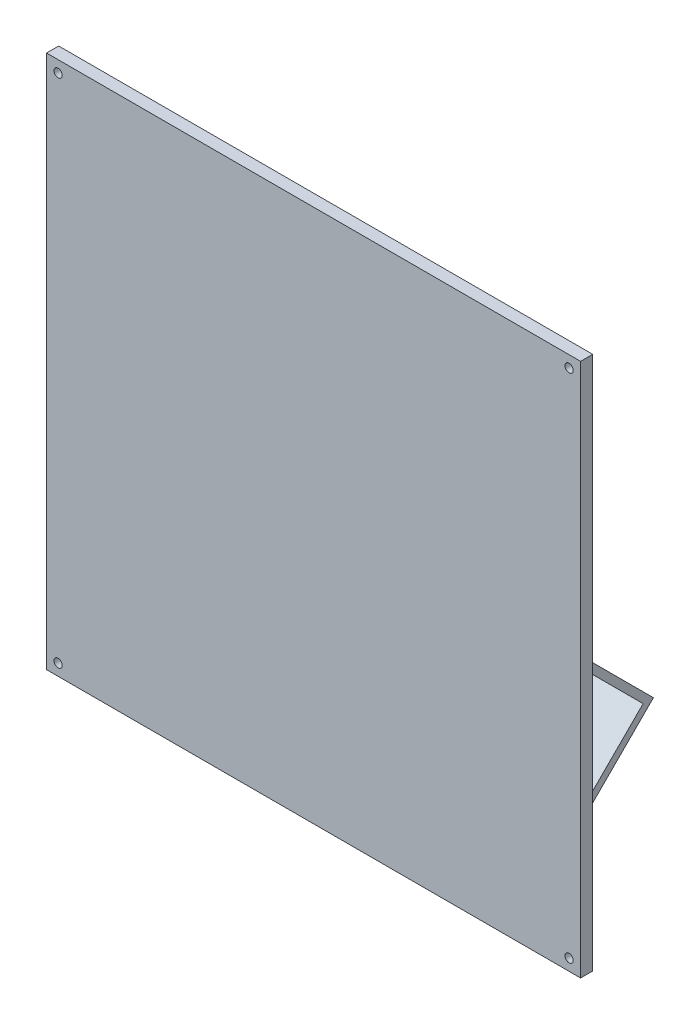
SolidWorks part; units mm, degrees
ref_plane "Přední rovina" through (0, 0, 0) normal (0, 0, 1) x (1, 0, 0)
ref_plane "Horní rovina" through (0, 0, 0) normal (0, 1, 0) x (1, 0, 0)
ref_plane "Pravá rovina" through (0, 0, 0) normal (1, 0, 0) x (0, 0, -1)
sketch "Skica1" plane through (0, 0, 0) normal (0, 0, 1) x (1, 0, 0)
  line L1 (-110, -110) -> (110, -110)
  line L2 (-110, -110) -> (-110, 110)
  line L3 (-110, 110) -> (110, 110)
  line L4 (110, -110) -> (110, 110)
  line L5 (-110, -110) -> (110, 110) construction
  line L6 (-110, 110) -> (110, -110) construction
  point P0 (0, 0)
  dimension "D1" = 220
  dimension "D2" = 220
extrude "Přidat vysunutím1" add sketch "Skica1" along normal blind 5
hole_wizard "Kuželové zahloubení pro M3 šroubu se zápustnou hlavou plochou1" positions "Skica5" profile "Skica4" countersink size "M3" standard "ISO" end condition through all
sketch "Skica5" plane through (0, 0, 0) normal (0, 0, -1) x (-1, 0, 0)
  line L0 (110, -110) -> (-110, -110) construction
  line L1 (-110, -110) -> (-110, 110) construction
  point P0 (-105.25, -105.25)
  dimension "D1" = 4.75
  dimension "D2" = 4.75
sketch "Skica4" plane through (105.25, -105.25, 0) normal (1, 0, 0) x (0, 1, 0)
  line L0 (0, 0) -> (0, 5)
  line L1 (0, 5) -> (1.7, 5)
  line L2 (1.7, 5) -> (1.7, 1.45)
  line L3 (1.7, 1.45) -> (3.15, 0)
  line L5 (3.15, 0) -> (0, 0)
  line L6 (-1.7, 1.45) -> (-3.15, 0) construction
  line L11 (0, -6.35) -> (0, 107.95) construction
  dimension "Průměr díry skrz" = 3.4
  dimension "Hloubka díry skrz" = 5
  dimension "Průměr blíz. kuž. zahloubení" = 6.3
  dimension "Úhel blíz. kuž. zahloubení" = 90
mirror "Zrcadlit1" about plane through (0, 0, 0) normal (0, 1, 0) of "Kuželové zahloubení pro M3 šroubu se zápustnou hlavou plochou1" second plane through (0, 0, 0) second plane normal (1, 0, 0)
sketch "Skica7" plane through (0, 0, 0) normal (0, 0, -1) x (-1, 0, 0)
  line L0 (0, 110) -> (0, -110) construction
  line L1 (-110, 110) -> (110, 110) construction
  line L2 (110, -110) -> (-110, -110) construction
  line L3 (-110, 0) -> (110, 0) construction
  line L4 (-110, -110) -> (-110, 110) construction
  line L5 (110, 110) -> (110, -110) construction
ref_plane "Rovina1" through (0, 0, 0) normal (0, -0.7071, 0.7071) x (-1, 0, 0)
sketch "Skica9" plane through (0, -110, 0) normal (0, -1, 0) x (1, 0, 0)
  line L0 (0, 51.3479) -> (0, -51.3479) construction
  point P4 (0, 0)
sketch "Skica15" plane through (0, 0, 0) normal (0, 0, -1) x (-1, 0, 0)
  line L0 (105, 0) -> (105, -2.5) construction
  line L2 (-110, 0) -> (110, 0) construction
  dimension "D1" = 2.5
  dimension "D2" = 5
sketch "Skica11" plane through (0, 0, 0) normal (0, -0.7071, 0.7071) x (-1, 0, 0)
  line L0 (-110, 0) -> (110, 0) construction
  line L1 (-80, 0) -> (80, 0)
  line L2 (-80, 0) -> (-80, 77.7817)
  line L3 (-80, 77.7817) -> (80, 77.7817)
  line L4 (80, 0) -> (80, 77.7817)
  dimension "D1" = 30
  dimension "D2" = 30
  dimension "D3" = 77.7817
extrude "Přidat vysunutím2" add sketch "Skica11" along normal blind 3
sketch "Skica17" plane through (0, -55, -55) normal (0, -0.7071, -0.7071) x (1, 0, 0)
  line L0 (-110, 77.7817) -> (110, 77.7817) construction
  line L1 (-80, 0) -> (80, 0)
  line L2 (-80, 0) -> (-80, 77.7817)
  line L3 (-80, 77.7817) -> (80, 77.7817)
  line L4 (80, 0) -> (80, 77.7817)
  line L5 (80, 3) -> (80, 0) construction
extrude "Přidat vysunutím3" add sketch "Skica17" against normal blind 3
